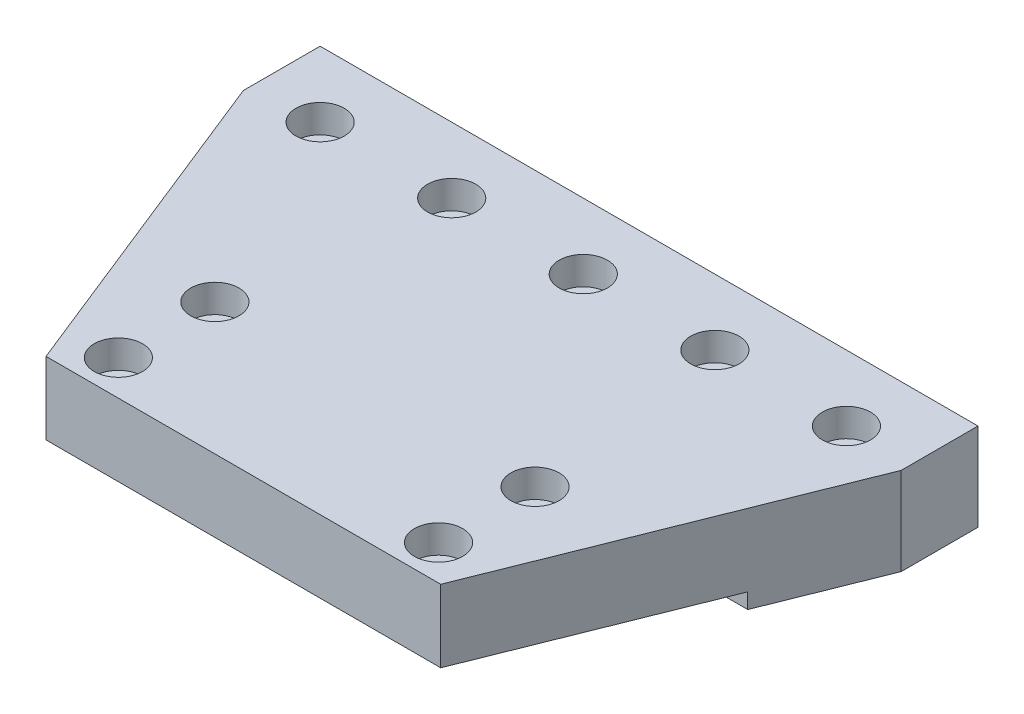
SolidWorks part; units mm, degrees
ref_plane "Front Plane" through (0, 0, 0) normal (0, 0, 1) x (1, 0, 0)
ref_plane "Top Plane" through (0, 0, 0) normal (0, 1, 0) x (1, 0, 0)
ref_plane "Right Plane" through (0, 0, 0) normal (1, 0, 0) x (0, 0, -1)
sketch "Sketch1" plane through (0, 0, 0) normal (0, 1, 0) x (1, 0, 0)
  line L1 (-75, 46.25) -> (75, 46.25)
  line L2 (-75, 46.25) -> (-75, -46.25)
  line L3 (-75, -46.25) -> (75, -46.25)
  line L4 (75, 46.25) -> (75, -46.25)
  line L5 (-75, 46.25) -> (75, -46.25) construction
  line L6 (-75, -46.25) -> (75, 46.25) construction
  point P0 (0, 0)
  dimension "D1" = 150
  dimension "D2" = 92.5
extrude "Boss-Extrude1" add sketch "Sketch1" along normal mid plane 20
chamfer "Chamfer2" distance 75 distance2 30 1 edges at (-75, 0, 46.25)
chamfer "Chamfer3" distance 30 distance2 75 1 edges at (75, 0, 46.25)
hole_wizard "CBORE for M6 Hex Socket Head Cap Screw1" positions "Sketch4" profile "Sketch5" counterbore size "M6" standard "ISO" end condition through all
sketch "Sketch4" plane through (0, 10, 0) normal (0, 1, 0) x (1, 0, 0)
  line L0 (-75, 46.25) -> (-75, 28.75) construction
  line L1 (75, 28.75) -> (75, 46.25) construction
  line L2 (75, 46.25) -> (-75, 46.25) construction
  point P0 (-60, 31.25)
  point P2 (-30, 31.25)
  point P4 (0, 31.25)
  point P6 (30, 31.25)
  point P8 (60, 31.25)
  dimension "D1" = 15
  dimension "D2" = 15
  dimension "D3" = 30
  dimension "D4" = 30
  dimension "D5" = 15
sketch "Sketch5" plane through (-60, 10, -31.25) normal (1, 0, 0) x (0, 0, 1)
  line L0 (0, 0) -> (0, 20)
  line L1 (0, 20) -> (3.3, 20)
  line L3 (3.3, 20) -> (3.3, 6.4)
  line L4 (3.3, 6.4) -> (5.5, 6.4)
  line L5 (5.5, 6.4) -> (5.5, 0)
  line L7 (5.5, 0) -> (0, 0)
  line L11 (0, -6.35) -> (0, 107.95) construction
  dimension "Thru Hole Dia." = 6.6
  dimension "Thru Hole Depth" = 20
  dimension "C'Bore Dia." = 11
  dimension "C'Bore Depth" = 6.4
hole_wizard "CBORE for M6 Hex Socket Head Cap Screw2" positions "Sketch8" profile "Sketch9" counterbore size "M6" standard "ISO" end condition through all
sketch "Sketch8" plane through (0, 10, 0) normal (0, 1, 0) x (1, 0, 0)
  line L0 (-45, -46.25) -> (45, -46.25) construction
  circle A0 centre (-60, 31.25) radius 5.5 construction
  point P0 (-36.5, -38.25)
  point P2 (-36.5, -16.25)
  point P4 (36.5, -16.25)
  point P6 (36.5, -38.25)
  dimension "D1" = 8
  dimension "D2" = 22
  dimension "D3" = 73
  dimension "D4" = 36.5
  dimension "D5" = 47.5
sketch "Sketch9" plane through (-36.5, 10, 38.25) normal (1, 0, 0) x (0, 0, 1)
  line L0 (0, 0) -> (0, 20)
  line L1 (0, 20) -> (3.3, 20)
  line L3 (3.3, 20) -> (3.3, 6.4)
  line L4 (3.3, 6.4) -> (5.5, 6.4)
  line L5 (5.5, 6.4) -> (5.5, 0)
  line L7 (5.5, 0) -> (0, 0)
  line L11 (0, -6.35) -> (0, 107.95) construction
  dimension "Thru Hole Dia." = 6.6
  dimension "Thru Hole Depth" = 20
  dimension "C'Bore Dia." = 11
  dimension "C'Bore Depth" = 6.4
sketch "Sketch11" plane through (0, -10, 0) normal (0, -1, 0) x (1, 0, 0)
  line L0 (-45, 46.25) -> (45, 46.25) construction
  line L1 (-75, 56.25) -> (75, 56.25)
  line L2 (-75, 56.25) -> (-75, -3.75)
  line L3 (-75, -3.75) -> (75, -3.75)
  line L4 (75, 56.25) -> (75, -3.75)
  dimension "D1" = 150
  dimension "D2" = 60
  dimension "D3" = 50
  dimension "D4" = 75
extrude "Cut-Extrude1" cut sketch "Sketch11" against normal blind 3.5 contours L2 L3 L4 L1
equation "\"D4@Sketch8\"=\"D3@Sketch8\"/2"
